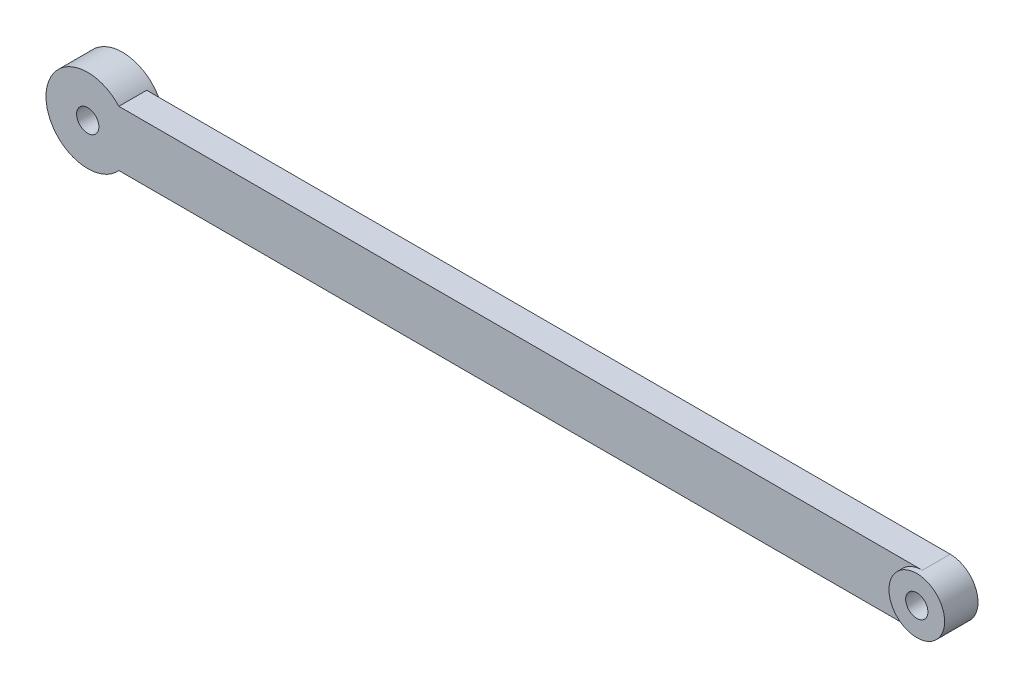
SolidWorks part; units mm, degrees
ref_plane "Ön Düzlem" through (0, 0, 0) normal (0, 0, 1) x (1, 0, 0)
ref_plane "Üst Düzlem" through (0, 0, 0) normal (0, 1, 0) x (1, 0, 0)
ref_plane "Sağ Düzlem" through (0, 0, 0) normal (1, 0, 0) x (0, 0, -1)
sketch "Sketch1" plane through (0, 0, 0) normal (0, 0, 1) x (1, 0, 0)
  line L0 (12.9904, 7.5) -> (293.3856, 7.5)
  line L1 (12.9904, -7.5) -> (293.3856, -7.5)
  circle A0 centre (0, 0) radius 15
  circle A1 centre (300, 0) radius 10
  dimension "D1" = 20
  dimension "D3" = 30
  dimension "D2" = 15
  dimension "D4" = 300
extrude "Boss-Extrude1" add sketch "Sketch1" along normal blind 10 contours A0 | A1
sketch "Sketch2" plane through (0, 0, 10) normal (0, 0, 1) x (1, 0, 0)
  circle A1 centre (0, 0) radius 15
  circle A2 centre (0, 0) radius 15
  dimension "D1" = 0
extrude "Boss-Extrude2" [suppressed] add sketch "Sketch2" along normal blind 10 draft 20
sketch "Sketch5" plane through (0, 0, 0) normal (0, 0, 1) x (1, 0, 0)
  line L0 (11.1803, 10) -> (300, 10)
  line L1 (300, -10) -> (11.1803, -10)
  circle A0 centre (0, 0) radius 15 construction
  circle A1 centre (300, 0) radius 10 construction
  circle A2 centre (0, 0) radius 15
  circle A3 centre (300, 0) radius 10
  dimension "D1" = 20
  dimension "D2" = 10
extrude "Boss-Extrude3" add sketch "Sketch5" along normal blind 10 contours A3 L0 A2 L1
sketch "Sketch6" [suppressed] plane through (0, 0, 5) normal (0, 0, 1) x (1, 0, 0)
  circle A1 centre (0, 0) radius 15 construction
  arc A3 (14.7902, -2.5) -> (14.7902, 2.5) centre (0, 0) ccw
extrude "Boss-Extrude4" [suppressed] add sketch "Sketch6" along normal blind 5
sketch "Sketch13" plane through (0, 0, 0) normal (0, 0, -1) x (-1, 0, 0)
  circle A0 centre (-300, 0) radius 4
  circle A1 centre (0, 0) radius 4
extrude "Cut-Extrude1" cut sketch "Sketch13" against normal blind 20
sketch "Sketch14" plane through (0, 0, 0) normal (0, 0, -1) x (-1, 0, 0)
  circle A0 centre (0, 0) radius 4
  circle A1 centre (0, 0) radius 15
extrude "Boss-Extrude7" add sketch "Sketch14" along normal blind 2.5
sketch "Sketch15" plane through (0, 0, 10) normal (0, 0, 1) x (1, 0, 0)
  circle A0 centre (300, 0) radius 4 construction
  arc A1 (300, -10) -> (300, 10) centre (300, 0) ccw construction
  circle A2 centre (300, 0) radius 4
  arc A3 (300, -10) -> (300, 10) centre (300, 0) ccw
  circle A4 centre (300, 0) radius 10
  circle M2 centre (300, 0) radius 4
  arc M3 (300, -10) -> (300, 10) centre (300, 0) ccw
extrude "Boss-Extrude8" add sketch "Sketch15" along normal blind 2 contours A4 M3 M2
scale "Echelle1" scale about centroid uniform scaling yes scale factor 0.6
